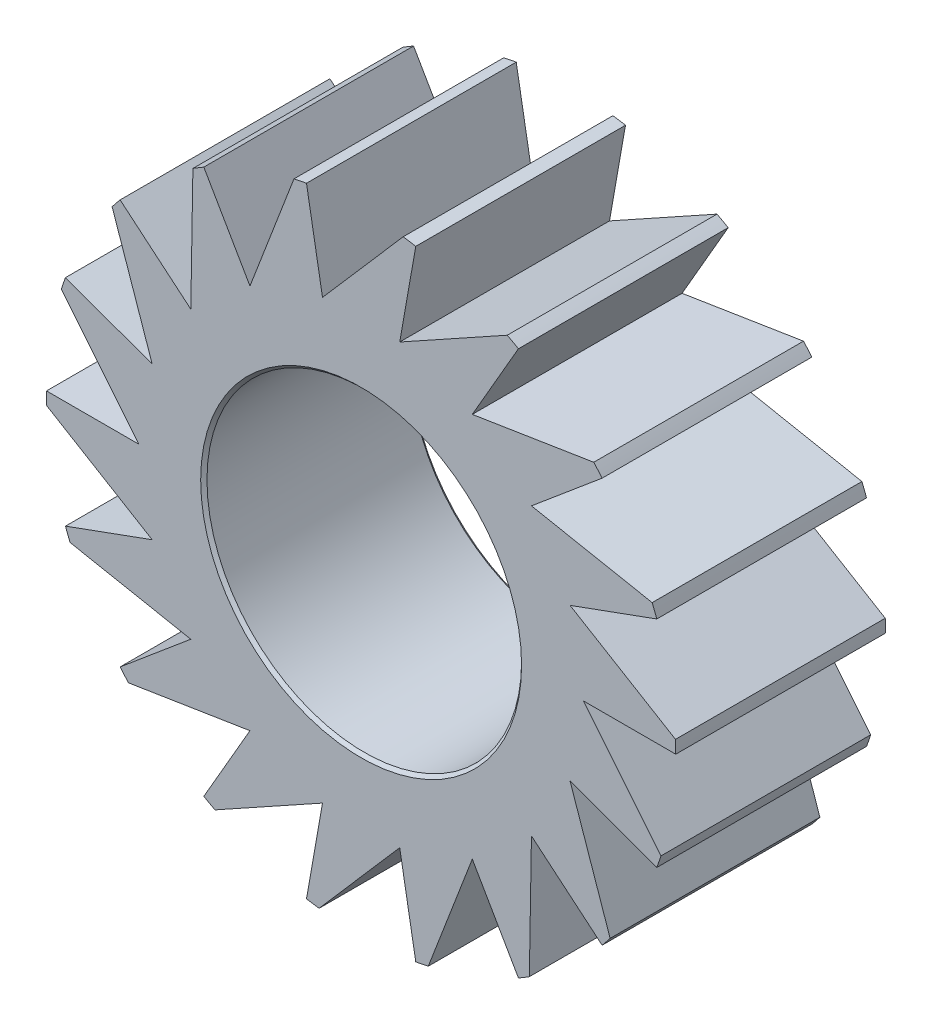
SolidWorks part; units mm, degrees
ref_plane "Front" through (0, 0, 0) normal (0, 0, 1) x (1, 0, 0)
ref_plane "Top" through (0, 0, 0) normal (0, 1, 0) x (1, 0, 0)
ref_plane "Right" through (0, 0, 0) normal (1, 0, 0) x (0, 0, -1)
sketch "Sketch1" plane through (0, 0, 0) normal (0, 0, 1) x (1, 0, 0)
  line L0 (-228.6, 0) -> (228.6, 0) construction
  circle A0 centre (0, 0) radius 9.525 construction
  circle A1 centre (0, 0) radius 10.16 construction
  circle A2 centre (0, 0) radius 4.7625
  circle A3 centre (0, 0) radius 6.731
  point P8 (0, 9.525)
  point P9 (0, -9.525)
  dimension "D1" = 13.462
  dimension "D2" = 20.32
extrude "Boss-Extrude1" add sketch "Sketch1" against normal blind 6.35
sketch "Sketch2" plane through (0, 0, 0) normal (0, 0, 1) x (1, 0, 0)
  line L0 (0, 0) -> (0, 9.525) construction
  line L1 (0, 0) -> (-1.1688, 6.6287) construction
  line L2 (0, 0) -> (1.7643, 10.0056) construction
  line L3 (-1.1688, 6.6287) -> (1.1688, 6.6287) construction
  line L4 (-1.1688, 6.6287) -> (1.7643, 10.0056)
  line L5 (1.7643, 10.0056) -> (1.1688, 6.6287)
  circle A0 centre (0, 0) radius 9.525 construction
  circle A1 centre (0, 0) radius 10.16 construction
  circle A2 centre (0, 0) radius 6.731 construction
  arc A4 (1.1688, 6.6287) -> (-1.1688, 6.6287) centre (0, 0) ccw
  point P11 (0, 6.6287)
  dimension "D1" = 20
extrude "Boss-Extrude2" add sketch "Sketch2" against normal blind 6.35
pattern_circular "CirPattern1" count 18 over 360 about axis through (0, 0, 0) along (0, 0, 1) of "Boss-Extrude2"
chamfer "Chamfer1" distance 0.0953 angle 45 2 edges at (4.7625, 0, -6.35) (4.7625, 0, 0)
sketch "Pawl" plane through (0, 0, 0) normal (0, 0, 1) x (1, 0, 0)
  line L0 (1.654, 9.3803) -> (4.4244, 8.4351) construction
  line L1 (1.1688, 6.6287) -> (1.7643, 10.0056) construction
  line L2 (5.08, 8.7988) -> (1.1688, 6.6287) construction
  circle A0 centre (0, 0) radius 9.525 construction
  point P9 (3.0392, 8.9077)
sketch_block_instance "Block1-1"
sketch_block "Block1"
sketch "Ref" plane through (0, 0, 0) normal (1, 0, 0) x (0, 0, -1)
  line L0 (0.0953, 4.7625) -> (6.2548, 4.7625) construction
  line L1 (6.2548, 4.7625) -> (6.35, 4.8578) construction
  line L2 (0.0953, 4.7625) -> (0, 4.8578) construction
  line L3 (0, 6.18) -> (0.0953, -4.7625) construction
  line L4 (0, 6.5307) -> (0, 5.8292) construction
  line L5 (0.0953, -4.7625) -> (6.2548, -4.7625) construction
  line L6 (6.2548, -4.7625) -> (6.35, -4.8578) construction
sketch "Sketch3" plane through (0, 0, 0) normal (0, 0, 1) x (1, 0, 0)
  circle A0 centre (0, 0) radius 9.525 construction
  circle A1 centre (0, 0) radius 9.525
extrude "Cut-Extrude-Thin1" cut sketch "Sketch3" against normal through all flip side to cut thin
equation "\"D1@Sketch2\" = 360/\"Teeth@Sketch1\""
equation "\"D1@Boss-Extrude2\" = \"D1@Boss-Extrude1\""
equation "\"D1@CirPattern1\" = \"Teeth@Sketch1\""
equation "\"D1@Chamfer1\" = \"Bore Dia.@Sketch1\"*.01"
equation "\"D1@Sketch1\"=\"OD@Sketch1\"-.22"
equation "\"D2@Sketch1\"=\"OD@Sketch1\"+.05"
